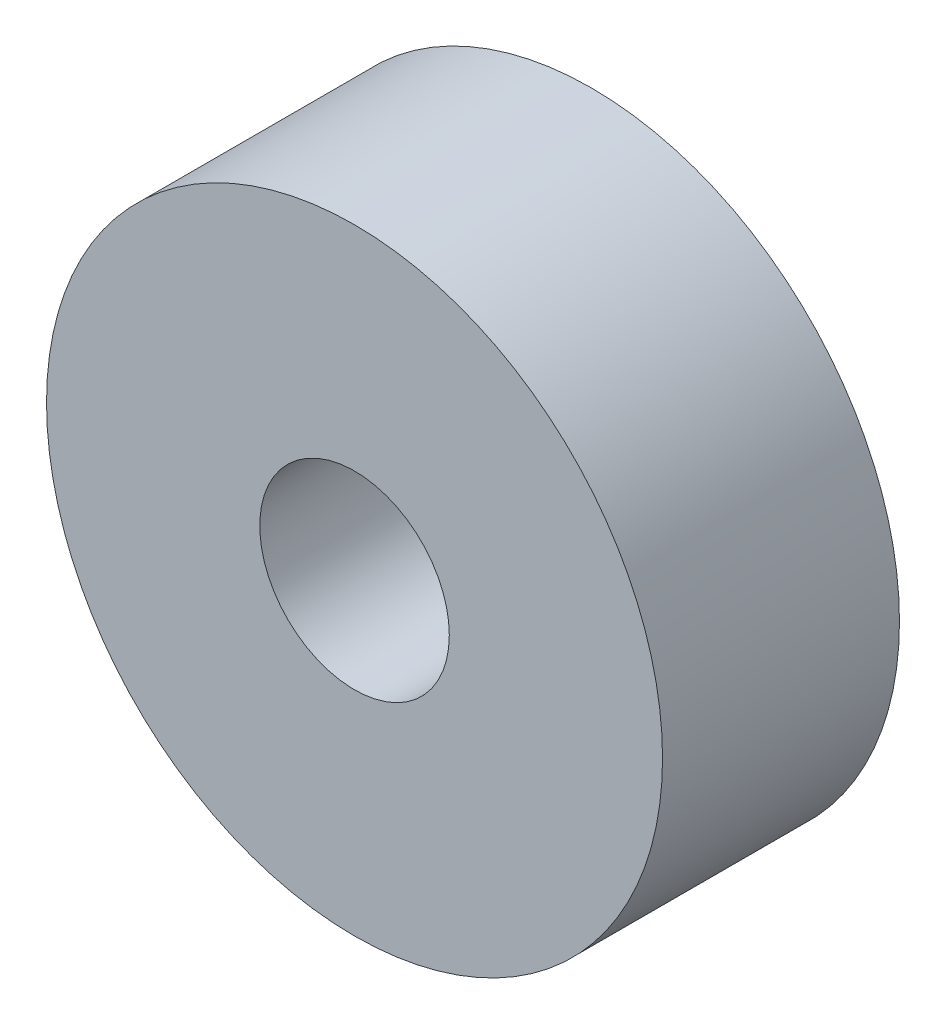
SolidWorks part; units mm, degrees
ref_plane "Front Plane" through (0, 0, 0) normal (0, 0, 1) x (1, 0, 0)
ref_plane "Top Plane" through (0, 0, 0) normal (0, 1, 0) x (1, 0, 0)
ref_plane "Right Plane" through (0, 0, 0) normal (1, 0, 0) x (0, 0, -1)
sketch "Sketch1" plane through (0, 0, 0) normal (0, 0, 1) x (1, 0, 0)
  circle A0 centre (0, 0) radius 2
  circle A1 centre (0, 0) radius 6.5
  dimension "D1" = 4
  dimension "D2" = 13
extrude "Boss-Extrude1" add sketch "Sketch1" along normal blind 5
